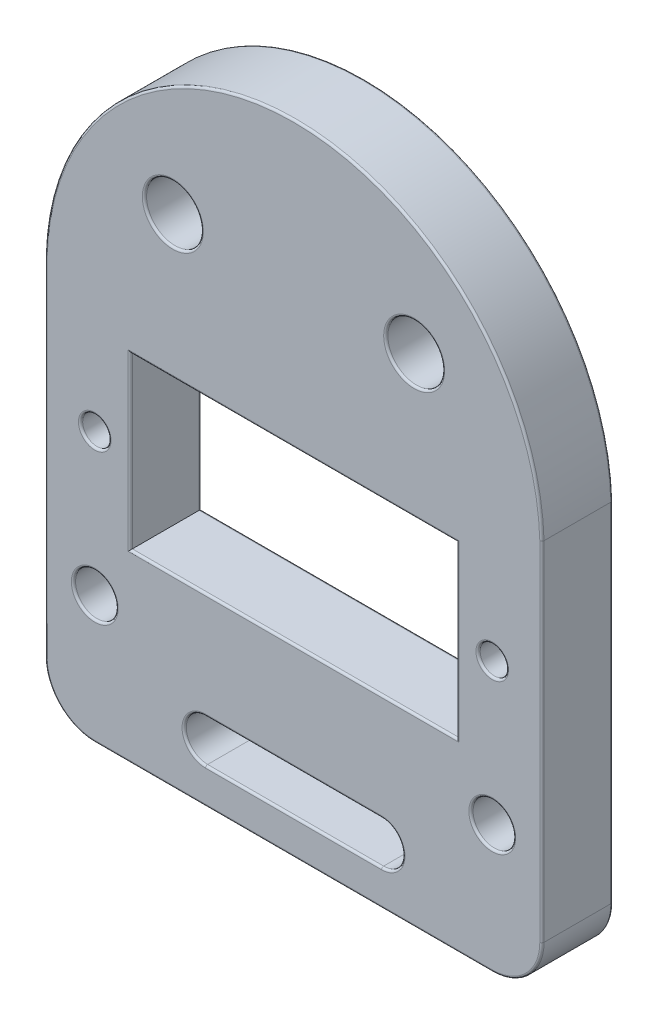
SolidWorks part; units mm, degrees
material "AISI 1020"
ref_plane "Front Plane" through (0, 0, 0) normal (0, 0, 1) x (1, 0, 0)
ref_plane "Top Plane" through (0, 0, 0) normal (0, 1, 0) x (1, 0, 0)
ref_plane "Right Plane" through (0, 0, 0) normal (1, 0, 0) x (0, 0, -1)
sketch "Sketch1" plane through (0, 0, 0) normal (0, 0, 1) x (1, 0, 0)
  line L0 (0, -19) -> (0, 26) construction
  line L1 (11.5, -6) -> (-11.5, -6)
  line L2 (11.5, -6) -> (11.5, 6)
  line L3 (11.5, 6) -> (-11.5, 6)
  line L4 (-11.5, -6) -> (-11.5, 6)
  line L5 (11.5, -6) -> (-11.5, 6) construction
  line L6 (11.5, 6) -> (-11.5, -6) construction
  line L7 (-6.2, -15) -> (6.2, -15) construction
  line L8 (-6.2, -13.5) -> (6.2, -13.5)
  line L9 (-6.2, -16.5) -> (6.2, -16.5)
  line L11 (-17.5, 9) -> (17.5, 9) construction
  line L12 (-17.5, 9) -> (-17.5, -19)
  line L13 (-17.5, -19) -> (17.5, -19)
  line L14 (17.5, 9) -> (17.5, -19)
  circle A0 centre (-14, 0) radius 1
  circle A1 centre (-14, -10) radius 1.5
  arc A2 (-6.2, -13.5) -> (-6.2, -16.5) centre (-6.2, -15) ccw
  arc A3 (6.2, -16.5) -> (6.2, -13.5) centre (6.2, -15) ccw
  circle A4 centre (-8.5, 16) radius 2
  circle A5 centre (14, -10) radius 1.5
  circle A6 centre (14, 0) radius 1
  circle A7 centre (8.5, 16) radius 2
  arc A8 (-17.5, 9) -> (17.5, 9) centre (0, 8.4926) cw
  point P0 (0, 0)
  point P10 (-11.5, 0)
  point P11 (0, -15)
  point P33 (0, 26)
  dimension "D5" = 2
  dimension "D7" = 3
  dimension "D9" = 1.5
  dimension "D12" = 10
  dimension "D13" = 4
  dimension "D1" = 23
  dimension "D2" = 12
  dimension "D3" = 45
  dimension "D4" = 13
  dimension "D6" = 2.5
  dimension "D8" = 10
  dimension "D10" = 12.4
  dimension "D11" = 4
  dimension "D14" = 8.5
  dimension "D15" = 28
  dimension "D16" = 35
  dimension "D17" = 13
extrude "Boss-Extrude1" add sketch "Sketch1" along normal blind 5
fillet "Fillet1" radius 3.5 2 edges at (17.5, -19, 2.5) (-17.5, -19, 2.5)
fillet "Fillet2" radius 0.15 40 edges at (6.5, 16, 0) (12.5, -10, 0) (7.7, -15, 0) (0, -16.5, 0) (-7.7, -15, 0) (0, -13.5, 0) (-12.5, -10, 0) (11.5, 0, 0) (0, -6, 0) (-11.5, 0, 0) (0, 6, 0) (0, 26, 0) (-17.5, -3.25, 0) (-16.4749, -17.9749, 0) (0, -19, 0) (16.4749, -17.9749, 0) (17.5, -3.25, 0) (-13, 0, 0) (-6.5, 16, 0) (13, 0, 0) (6.5, 16, 5) (13, 0, 5) (12.5, -10, 5) (-6.5, 16, 5) (0, -16.5, 5) (7.7, -15, 5) (0, -13.5, 5) (-7.7, -15, 5) (-16.4749, -17.9749, 5) (-17.5, -3.25, 5) (0, 26, 5) (17.5, -3.25, 5) (16.4749, -17.9749, 5) (0, -19, 5) (0, -6, 5) (11.5, 0, 5) (0, 6, 5) (-11.5, 0, 5) (-13, 0, 5) (-12.5, -10, 5)
